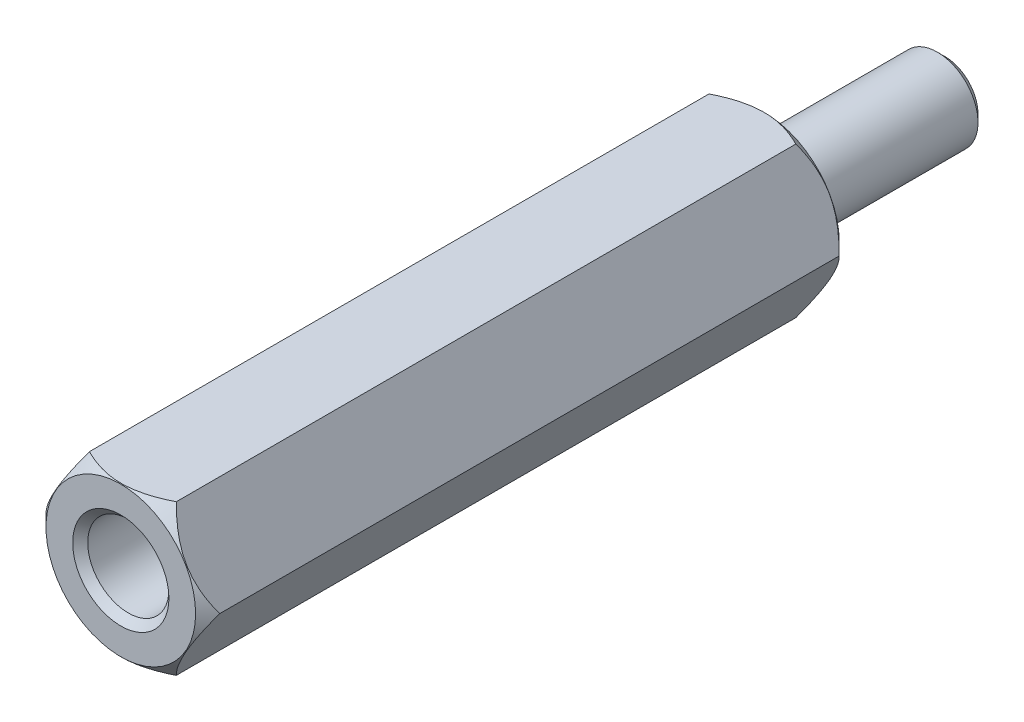
SolidWorks part; units mm, degrees
material "Brass"
ref_plane "Front Plane" through (0, 0, 0) normal (0, 0, 1) x (1, 0, 0)
ref_plane "Top Plane" through (0, 0, 0) normal (0, 1, 0) x (1, 0, 0)
ref_plane "Right Plane" through (0, 0, 0) normal (1, 0, 0) x (0, 0, -1)
ref_axis "Axis1" through (0, 0, 15.2667) along (0, 0, -1)
sketch "Sketch1" plane through (0, 0, 0) normal (0, 0, 1) x (1, 0, 0)
  line L1 (2.8868, 0) -> (1.4434, 2.5)
  line L2 (1.4434, 2.5) -> (-1.4434, 2.5)
  line L3 (-1.4434, 2.5) -> (-2.8868, 0)
  line L4 (-2.8868, 0) -> (-1.4434, -2.5)
  line L5 (-1.4434, -2.5) -> (1.4434, -2.5)
  line L6 (1.4434, -2.5) -> (2.8868, 0)
  circle A0 centre (0, 0) radius 2.5 construction
  dimension "D1" = 5
extrude "HEX" add sketch "Sketch1" along normal mid plane 21.4
hole_wizard "Tap Drill for M3x0.5 Tap1" positions "Sketch5" profile "Sketch6" hole size "M3x0.5" standard "BSI" end condition through all
sketch "Sketch5" plane through (0, 0, 10.7) normal (0, 0, 1) x (1, 0, 0)
  point P0 (0, 0)
sketch "Sketch6" plane through (0, 0, 10.7) normal (1, 0, 0) x (0, -1, 0)
  line L0 (0, 0) -> (0, 21.4)
  line L1 (0, 21.4) -> (1.35, 21.4)
  line L2 (1.35, 21.4) -> (1.35, 0)
  line L5 (1.35, 0) -> (0, 0)
  line L11 (0, -6.35) -> (0, 107.95) construction
  dimension "Thru Hole Dia." = 2.7
  dimension "Thru Hole Depth" = 21.4
sketch "Sketch7" plane through (0, 0, 0) normal (0, 1, 0) x (1, 0, 0)
  line L0 (-2.8868, 10.7) -> (-2.8868, 10.3)
  line L1 (-2.8868, -10.7) -> (-2.8868, 10.7) construction
  line L2 (-2.8868, 10.7) -> (-2.4868, 10.7)
  line L3 (-1.4434, 10.7) -> (-2.8868, 10.7) construction
  line L4 (-2.4868, 10.7) -> (-2.8868, 10.3)
  dimension "D1" = 0.4
revolve "HexChamfer" cut sketch "Sketch7" angle 360 about axis through (0, 0, 15.2667) along (0, 0, -1)
mirror "Mirror1" about plane through (0, 0, 0) normal (0, 0, 1) of "HexChamfer"
sketch "Sketch8" plane through (0, 0, -10.7) normal (0, 0, -1) x (-1, 0, 0)
  circle A0 centre (0, 0) radius 1.35
  dimension "D1" = 2.7
extrude "Thread" add sketch "Sketch8" along normal blind 6 and the other way blind 2
chamfer "InnerChamfer" distance 0.25 angle 45 3 edges at (1.35, 0, 10.7) (-1.35, 0, -16.7) (1.35, 0, -10.7)
